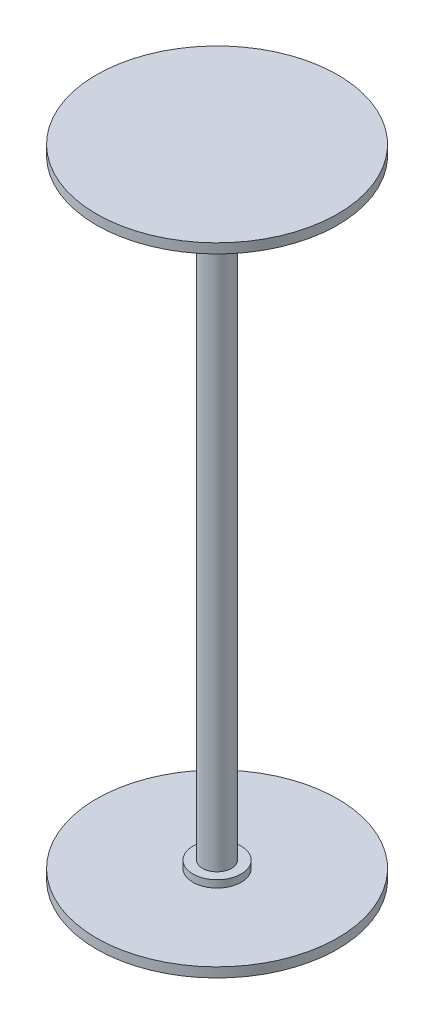
SolidWorks part; units mm, degrees
ref_plane "Front Plane" through (0, 0, 0) normal (0, 0, 1) x (1, 0, 0)
ref_plane "Top Plane" through (0, 0, 0) normal (0, 1, 0) x (1, 0, 0)
ref_plane "Right Plane" through (0, 0, 0) normal (1, 0, 0) x (0, 0, -1)
sketch "Sketch1" plane through (0, 0, 0) normal (0, 1, 0) x (1, 0, 0)
  circle A0 centre (0, 0) radius 25
  dimension "D1" = 50
extrude "Boss-Extrude1" add sketch "Sketch1" along normal blind 2 contours A0
sketch "Sketch2" plane through (0, 2, 0) normal (0, 1, 0) x (1, 0, 0)
  circle A0 centre (0, 0) radius 5
  dimension "D1" = 10
extrude "Boss-Extrude2" add sketch "Sketch2" along normal blind 1.5
sketch "Sketch3" plane through (0, 3.5, 0) normal (0, 1, 0) x (1, 0, 0)
  circle A0 centre (0, 0) radius 3
  dimension "D1" = 6
extrude "Boss-Extrude3" add sketch "Sketch3" along normal blind 62.5
sketch "Sketch4" plane through (0, 66, 0) normal (0, 1, 0) x (1, 0, 0)
  circle A0 centre (0, 0) radius 1.05
  dimension "D1" = 2.1
extrude "Cut-Extrude1" cut sketch "Sketch4" against normal blind 9
mirror "Mirror6" about plane through (0, 66, 0) normal (0, 1, 0) of bodies 104
